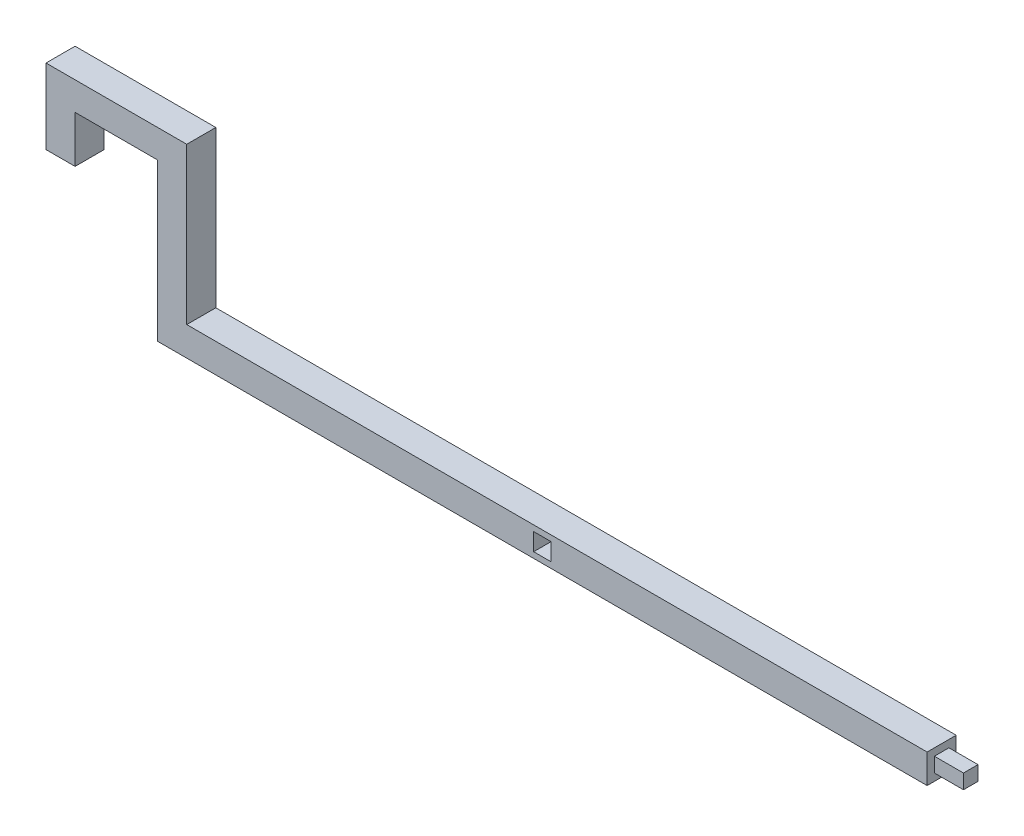
SolidWorks part; units mm, degrees
ref_plane "Front Plane" through (0, 0, 0) normal (0, 0, 1) x (1, 0, 0)
ref_plane "Top Plane" through (0, 0, 0) normal (0, 1, 0) x (1, 0, 0)
ref_plane "Right Plane" through (0, 0, 0) normal (1, 0, 0) x (0, 0, -1)
sketch "Sketch1" plane through (0, 0, 0) normal (0, 0, 1) x (1, 0, 0)
  line L0 (0, 6.7) -> (0, 8.05)
  line L5 (0, 0) -> (-5, 0)
  line L6 (-5, 0) -> (-5, 12.9)
  line L7 (-5, 12.9) -> (5.5, 12.9)
  line L8 (0, 8.05) -> (5.5, 8.05)
  line L10 (5.5, 12.9) -> (19.2, 12.9)
  line L11 (5.5, 8.05) -> (14.2, 8.05)
  line L16 (0, 6.7) -> (0, 0)
  line L17 (14.2, 8.05) -> (14.2, -18.95)
  line L18 (14.2, -18.95) -> (146.5, -18.95)
  line L19 (19.2, 12.9) -> (19.2, -13.95)
  line L20 (146.5, -18.95) -> (146.5, -13.95)
  line L21 (19.2, -13.95) -> (146.5, -13.95)
  dimension "D1" = 6.7
  dimension "D2" = 27
  dimension "D3" = 1.35
  dimension "D4" = 5
  dimension "D5" = 4.85
  dimension "D6" = 5
  dimension "D7" = 14.2
  dimension "D8" = 4.85
  dimension "D9" = 5
  dimension "D10" = 5
  dimension "D13" = 6.7
  dimension "D16" = 132.3
extrude "Boss-Extrude1" add sketch "Sketch1" along normal blind 5
sketch "Sketch2" plane through (146.5, 0, 0) normal (1, 0, 0) x (0, 0, -1)
  line L0 (-5, -18.95) -> (-5, -13.95) construction
  line L1 (-3.75, -17.7) -> (-1.25, -17.7)
  line L2 (-3.75, -17.7) -> (-3.75, -15.2)
  line L3 (-3.75, -15.2) -> (-1.25, -15.2)
  line L4 (-1.25, -17.7) -> (-1.25, -15.2)
  line L6 (-5, -13.95) -> (0, -13.95) construction
  point P4 (-3.75, -16.45)
  dimension "D1" = 2.5
  dimension "D2" = 2.5
  dimension "D3" = 1.25
  dimension "D4" = 1.25
extrude "Boss-Extrude2" add sketch "Sketch2" along normal blind 5
sketch "Sketch3" plane through (0, 0, 5) normal (0, 0, 1) x (1, 0, 0)
  line L0 (14.2, -18.95) -> (146.5, -18.95) construction
  line L1 (78.85, -14.95) -> (81.85, -14.95)
  line L2 (78.85, -14.95) -> (78.85, -17.95)
  line L3 (78.85, -17.95) -> (81.85, -17.95)
  line L4 (81.85, -14.95) -> (81.85, -17.95)
  dimension "D1" = 3
  dimension "D2" = 3
  dimension "D3" = 1
  dimension "D4" = 64.65
extrude "Cut-Extrude1" cut sketch "Sketch3" against normal blind 21
